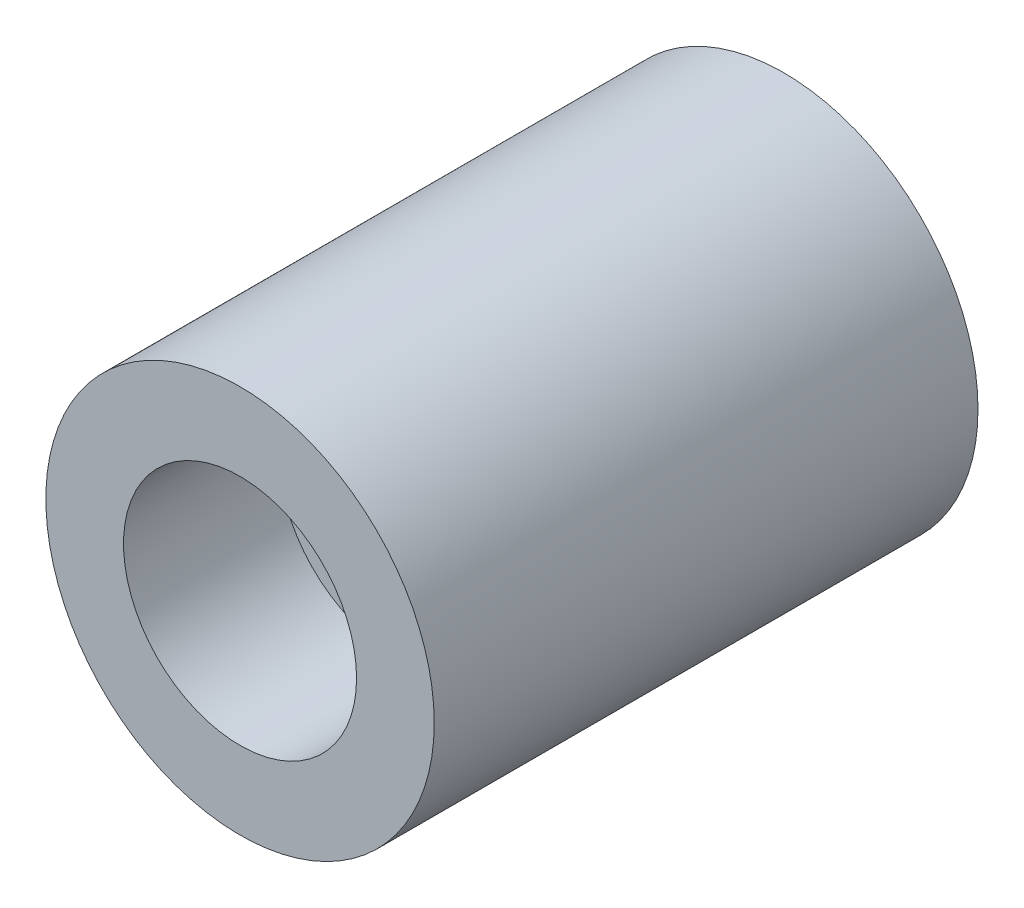
SolidWorks part; units mm, degrees
ref_plane "Front Plane" through (0, 0, 0) normal (0, 0, 1) x (1, 0, 0)
ref_plane "Top Plane" through (0, 0, 0) normal (0, 1, 0) x (1, 0, 0)
ref_plane "Right Plane" through (0, 0, 0) normal (1, 0, 0) x (0, 0, -1)
sketch "Sketch1" plane through (0, 0, 0) normal (0, 0, 1) x (1, 0, 0)
  circle A0 centre (0, 0) radius 1270
  dimension "D1" = 2540
extrude "Boss-Extrude1" add sketch "Sketch1" along normal blind 3556
sketch "Sketch2" plane through (0, 0, 3556) normal (0, 0, 1) x (1, 0, 0)
  circle A0 centre (0, 0) radius 762
  dimension "D1" = 1524
extrude "Cut-Extrude1" cut sketch "Sketch2" against normal blind 1016
sketch "Sketch3" plane through (0, 0, 2540) normal (0, 0, 1) x (1, 0, 0)
  circle A0 centre (0, 0) radius 254
  dimension "D1" = 508
extrude "Cut-Extrude2" cut sketch "Sketch3" against normal blind 2032
